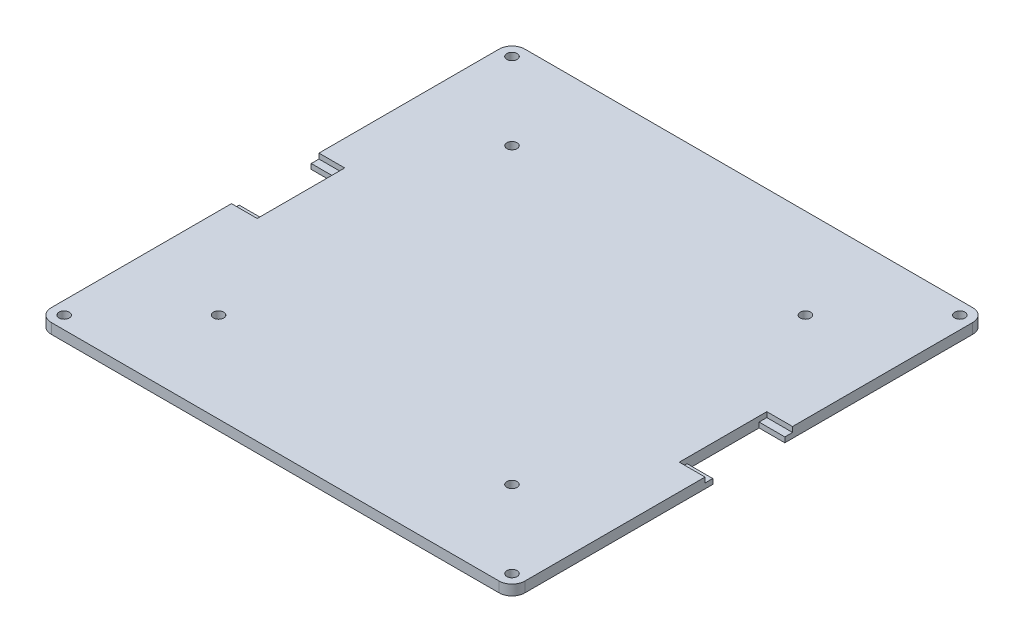
SolidWorks part; units mm, degrees
ref_plane "Front Plane" through (0, 0, 0) normal (0, 0, 1) x (1, 0, 0)
ref_plane "Top Plane" through (0, 0, 0) normal (0, 1, 0) x (1, 0, 0)
ref_plane "Right Plane" through (0, 0, 0) normal (1, 0, 0) x (0, 0, -1)
sketch "Sketch2" plane through (0, 0, 0) normal (0, 1, 0) x (1, 0, 0)
  line L1 (-43.5, -47.5) -> (43.5, -47.5)
  line L2 (-47.5, -43.5) -> (-47.5, 43.5)
  line L3 (-43.5, 47.5) -> (43.5, 47.5)
  line L4 (47.5, -43.5) -> (47.5, 43.5)
  line L5 (-43.5, -43.5) -> (43.5, 43.5) construction
  line L6 (-43.5, 43.5) -> (43.5, -43.5) construction
  arc A0 (-43.5, -47.5) -> (-47.5, -43.5) centre (-43.5, -43.5) cw
  arc A1 (43.5, -47.5) -> (47.5, -43.5) centre (43.5, -43.5) ccw
  arc A2 (43.5, 47.5) -> (47.5, 43.5) centre (43.5, 43.5) cw
  arc A3 (-47.5, 43.5) -> (-43.5, 47.5) centre (-43.5, 43.5) cw
  point P0 (0, 0)
  dimension "D1" = 4
  dimension "D2" = 95
sketch "Sketch3" plane through (0, 0, 0) normal (0, 0, 1) x (1, 0, 0)
  line L0 (0, 0) -> (0, -1.6)
  line L1 (-43.5, 0) -> (43.5, 0) construction
  line L2 (0, -1.6) -> (0, -8.5)
  line L3 (0, -8.5) -> (0, -10)
  dimension "D1" = 1.6
  dimension "D2" = 10
  dimension "D3" = 1.5
sketch "Sketch4" plane through (0, 0, 0) normal (0, 1, 0) x (1, 0, 0)
  line L19 (-46.5, 43.5) -> (-46.5, -43.5)
  line L20 (-43.5, -46.5) -> (43.5, -46.5)
  line L21 (46.5, -43.5) -> (46.5, 43.5)
  line L22 (43.5, 46.5) -> (-43.5, 46.5)
  line L23 (-46.5, 43.5) -> (-46.5, -43.5)
  line L24 (-43.5, -46.5) -> (43.5, -46.5)
  line L25 (46.5, -43.5) -> (46.5, 43.5)
  line L26 (43.5, 46.5) -> (-43.5, 46.5)
  arc A16 (-46.5, -43.5) -> (-43.5, -46.5) centre (-43.5, -43.5) ccw
  arc A17 (43.5, -46.5) -> (46.5, -43.5) centre (43.5, -43.5) ccw
  arc A18 (46.5, 43.5) -> (43.5, 46.5) centre (43.5, 43.5) ccw
  arc A19 (-43.5, 46.5) -> (-46.5, 43.5) centre (-43.5, 43.5) ccw
  arc A20 (-46.5, -43.5) -> (-43.5, -46.5) centre (-43.5, -43.5) ccw
  arc A21 (43.5, -46.5) -> (46.5, -43.5) centre (43.5, -43.5) ccw
  arc A22 (46.5, 43.5) -> (43.5, 46.5) centre (43.5, 43.5) ccw
  arc A23 (-43.5, 46.5) -> (-46.5, 43.5) centre (-43.5, 43.5) ccw
  dimension "D1" = 1
sketch "Sketch5" plane through (0, 0, 0) normal (1, 0, 0) x (0, 0, -1)
  line L1 (-7, -5) -> (7, -5)
  line L2 (-7, -5) -> (-7, -10)
  line L3 (-7, -10) -> (7, -10)
  line L4 (7, -5) -> (7, -10)
  line L5 (0, -8.5) -> (0, -10) construction
  line L6 (0, -8.5) -> (0, -10) construction
  dimension "D1" = 14
  dimension "D2" = 5
ref_plane "Plane1" through (0, -10, 0) normal (0, 1, 0) x (1, 0, 0)
sketch "Sketch6" plane through (0, -10, 0) normal (0, 1, 0) x (1, 0, 0)
  line L0 (-41, 0) -> (0, 0) construction
  line L1 (-43.5, -43.5) -> (43.5, 43.5) construction
  line L2 (-46, -7) -> (-46, -43.5)
  line L3 (0, 0) -> (0, -32.2074) construction
  line L4 (-46, 7) -> (-41, 7)
  line L5 (-41, 7) -> (-41, -7)
  line L6 (-41, -7) -> (-46, -7)
  line L7 (41, -7) -> (46, -7)
  line L8 (-43.5, -46) -> (43.5, -46)
  line L9 (46, -43.5) -> (46, 43.5)
  line L10 (43.5, 46) -> (-43.5, 46)
  line L11 (-46, 43.5) -> (-46, -43.5)
  line L12 (-43.5, -46) -> (43.5, -46)
  line L13 (46, -43.5) -> (46, -7)
  line L14 (43.5, 46) -> (-43.5, 46)
  line L15 (-46, 43.5) -> (-46, 7)
  line L16 (41, 7) -> (41, -7)
  line L17 (46, 7) -> (41, 7)
  line L18 (46, 7) -> (46, 43.5)
  arc A8 (43.5, -46) -> (46, -43.5) centre (43.5, -43.5) ccw
  arc A9 (46, 43.5) -> (43.5, 46) centre (43.5, 43.5) ccw
  arc A10 (-43.5, 46) -> (-46, 43.5) centre (-43.5, 43.5) ccw
  arc A11 (-46, -43.5) -> (-43.5, -46) centre (-43.5, -43.5) ccw
  arc A12 (43.5, -46) -> (46, -43.5) centre (43.5, -43.5) ccw
  arc A13 (46, 43.5) -> (43.5, 46) centre (43.5, 43.5) ccw
  arc A14 (-43.5, 46) -> (-46, 43.5) centre (-43.5, 43.5) ccw
  arc A15 (-46, -43.5) -> (-43.5, -46) centre (-43.5, -43.5) ccw
  dimension "D2" = 14
  dimension "D3" = 5
  dimension "D1" = 1.5
extrude "Boss-Extrude1" add sketch "Sketch6" along normal blind 2
sketch "Sketch7" plane through (0, -8, 0) normal (0, 1, 0) x (1, 0, 0)
  line L0 (-46, 43.5) -> (-46, 7) construction
  line L1 (0, 0) -> (0, 19.7939) construction
  line L2 (-41, 7) -> (-46, 7)
  line L3 (-41, 7) -> (-41, 8.5)
  line L4 (-41, 8.5) -> (-46, 8.5)
  line L5 (-46, 7) -> (-46, 8.5)
  line L6 (-46, -7) -> (-46, -43.5) construction
  line L7 (-41, -7) -> (-46, -7)
  line L8 (-41, -7) -> (-41, -8.5)
  line L9 (-41, -8.5) -> (-46, -8.5)
  line L10 (-46, -7) -> (-46, -8.5)
  line L11 (41, -8.5) -> (46, -8.5)
  line L12 (46, -7) -> (46, -8.5)
  line L13 (41, -7) -> (46, -7)
  line L14 (41, -7) -> (41, -8.5)
  line L15 (41, 8.5) -> (46, 8.5)
  line L16 (46, 7) -> (46, 8.5)
  line L17 (41, 7) -> (46, 7)
  line L18 (41, 7) -> (41, 8.5)
  dimension "D1" = 17
extrude "Cut-Extrude1" cut sketch "Sketch7" against normal offset from surface (1 mm away) 1 up to face at (0, -10, 0)
sketch "Sketch8" plane through (0, -8, 0) normal (0, 1, 0) x (1, 0, 0)
  line L0 (-43.5, 43.5) -> (43.5, -43.5) construction
  line L1 (-43.5, -43.5) -> (43.5, 43.5) construction
  line L2 (28.5, 28.5) -> (-28.5, 28.5) construction
  line L3 (-28.5, 28.5) -> (-28.5, -28.5) construction
  line L4 (-28.5, -28.5) -> (28.5, -28.5) construction
  circle A0 centre (-43.5, 43.5) radius 1
  circle A1 centre (43.5, 43.5) radius 1
  circle A2 centre (-43.5, -43.5) radius 1
  circle A3 centre (43.5, -43.5) radius 1
  circle A4 centre (-28.5, 28.5) radius 1
  circle A5 centre (28.5, 28.5) radius 1
  circle A6 centre (-28.5, -28.5) radius 1
  circle A7 centre (28.5, -28.5) radius 1
  dimension "D1" = 2
  dimension "D2" = 57
extrude "Cut-Extrude2" cut sketch "Sketch8" against normal blind 5
